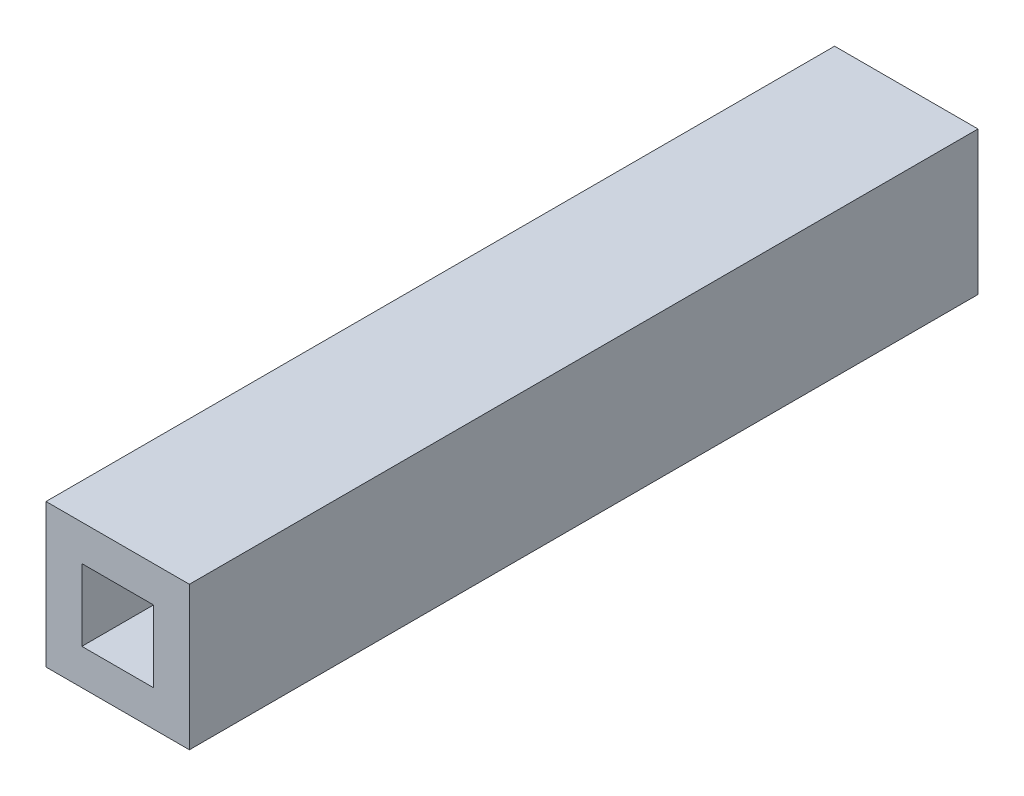
SolidWorks part; units mm, degrees
material "6063-O"
ref_plane "Front Plane" through (0, 0, 0) normal (0, 0, 1) x (1, 0, 0)
ref_plane "Top Plane" through (0, 0, 0) normal (0, 1, 0) x (1, 0, 0)
ref_plane "Right Plane" through (0, 0, 0) normal (1, 0, 0) x (0, 0, -1)
sketch "Sketch1" plane through (0, 0, 0) normal (0, 0, 1) x (1, 0, 0)
  line L1 (-10, -10) -> (10, -10)
  line L2 (-10, -10) -> (-10, 10)
  line L3 (-10, 10) -> (10, 10)
  line L4 (10, -10) -> (10, 10)
  line L5 (-10, -10) -> (10, 10) construction
  line L6 (-10, 10) -> (10, -10) construction
  point P0 (0, 0)
  dimension "D1" = 20
extrude "Extrude-Thin1" add sketch "Sketch1" along normal blind 110 thin thin type one direction reverse wall 5
